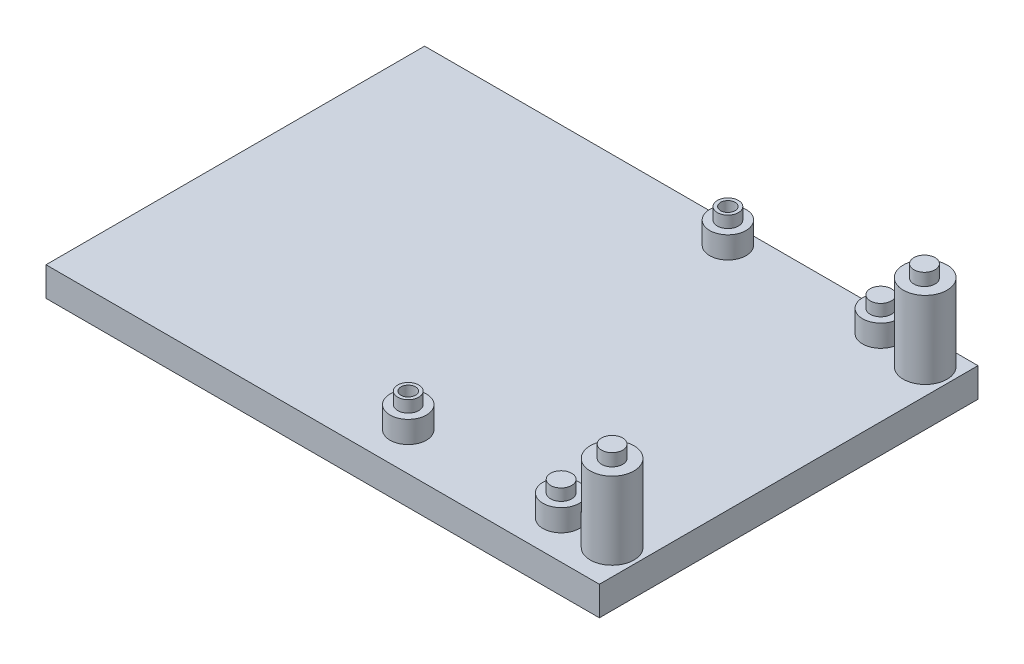
SolidWorks part; units mm, degrees
ref_plane "Front Plane" through (0, 0, 0) normal (0, 0, 1) x (1, 0, 0)
ref_plane "Top Plane" through (0, 0, 0) normal (0, 1, 0) x (1, 0, 0)
ref_plane "Right Plane" through (0, 0, 0) normal (1, 0, 0) x (0, 0, -1)
sketch "Sketch1" plane through (0, 0, 0) normal (0, 1, 0) x (1, 0, 0)
  line L0 (36, 0) -> (36, 44) construction
  line L1 (0, 0) -> (72, 0)
  line L2 (0, 0) -> (0, 44)
  line L3 (0, 44) -> (72, 44)
  line L4 (72, 0) -> (72, 44)
  line L6 (-2, -2) -> (74, -2)
  line L7 (-2, -2) -> (-2, 46)
  line L8 (-2, 46) -> (74, 46)
  line L9 (74, -2) -> (74, 46)
  line L10 (-2, -2) -> (74, 46) construction
  line L11 (-2, 46) -> (74, -2) construction
  point P7 (36, 22)
  dimension "D1" = 44
  dimension "D2" = 72
  dimension "D3" = 2
  dimension "D4" = 2
extrude "Boss-Extrude1" add sketch "Sketch1" along normal blind 2
sketch "Sketch2" plane through (0, 2, 0) normal (0, 1, 0) x (1, 0, 0)
  line L1 (-2, -2) -> (74, -2)
  line L2 (-2, -2) -> (-2, 46)
  line L3 (-2, 46) -> (74, 46)
  line L4 (74, -2) -> (74, 46)
extrude "Boss-Extrude2" add sketch "Sketch2" along normal blind 2
sketch "Sketch8" plane through (0, 0, -46) normal (0, 0, -1) x (-1, 0, 0)
  line L1 (2, 0) -> (-74, 0)
  line L2 (2, 0) -> (2, 4)
  line L3 (2, 4) -> (-74, 4)
  line L4 (-74, 0) -> (-74, 4)
extrude "Boss-Extrude7" add sketch "Sketch8" along normal blind 4
sketch "Sketch3" plane through (0, 4, 0) normal (0, 1, 0) x (1, 0, 0)
  line L0 (42.5, -2) -> (42.5, 3.25) construction
  line L1 (-2, -2) -> (74, -2) construction
  line L2 (42.5, 3.25) -> (74, 3.25) construction
  line L3 (74, -2) -> (74, 50) construction
  line L4 (42.5, 4.75) -> (42.5, 45.65) construction
  line L5 (42.5, 47.15) -> (63.5, 47.15) construction
  line L6 (63.5, 47.15) -> (63.5, 3.25) construction
  line L7 (70.5, 3.25) -> (70.5, 47.15) construction
  line L8 (70.5, 47.15) -> (63.5, 47.15) construction
  circle A0 centre (42.5, 3.25) radius 2.5
  circle A1 centre (63.5, 3.25) radius 2.5
  circle A2 centre (42.5, 47.15) radius 2.5
  circle A3 centre (63.5, 47.15) radius 2.5
  circle A4 centre (42.5, 3.25) radius 1
  circle A7 centre (42.5, 47.15) radius 1
  circle A8 centre (42.5, 47.15) radius 1.5 construction
  circle A9 centre (42.5, 3.25) radius 1.5 construction
  dimension "D3" = 5
  dimension "D4" = 2
  dimension "D6" = 3
  dimension "D8" = 3.5
  dimension "D2" = 5.25
  dimension "D5" = 21
  dimension "D7" = 40.9
  dimension "D9" = 28
extrude "Boss-Extrude3" add sketch "Sketch3" along normal blind 3
sketch "Sketch4" plane through (0, 7, 0) normal (0, 1, 0) x (1, 0, 0)
  circle A0 centre (42.5, 3.25) radius 1
  circle A1 centre (42.5, 3.25) radius 1.45
  circle A5 centre (42.5, 47.15) radius 1.45
  circle A8 centre (42.5, 47.15) radius 1
  circle A9 centre (63.5, 3.25) radius 1.45
  circle A10 centre (63.5, 47.15) radius 1.45
  dimension "D1" = 2.9
extrude "Boss-Extrude4" add sketch "Sketch4" along normal blind 1.6
sketch "Sketch5" plane through (0, 4, 0) normal (0, 1, 0) x (1, 0, 0)
  circle A0 centre (70.5, 3.25) radius 3
  circle A1 centre (70.5, 46.25) radius 3
  dimension "D2" = 6
  dimension "D1" = 43
extrude "Boss-Extrude5" add sketch "Sketch5" along normal blind 10.6
sketch "Sketch7" plane through (0, 14.6, 0) normal (0, 1, 0) x (1, 0, 0)
  line L0 (70.5, 46.25) -> (70.5, 46.15) construction
  circle A0 centre (70.5, 3.25) radius 1.45
  circle A1 centre (70.5, 46.15) radius 1.45
  circle A2 centre (70.5, 3.25) radius 3 construction
  dimension "D1" = 2.9
  dimension "D2" = 0.1
extrude "Boss-Extrude6" add sketch "Sketch7" along normal blind 1.7
sketch "Sketch9" plane through (0, 4, 0) normal (0, 1, 0) x (1, 0, 0)
  line L0 (5.5, -2) -> (5.5, 12) construction
  line L1 (-2, -2) -> (74, -2) construction
  line L2 (5.5, 12) -> (-2, 12) construction
  line L3 (-2, 50) -> (-2, -2) construction
  line L4 (15.5, 32) -> (15.5, 12) construction
  line L5 (5.5, 12) -> (25.5, 12) construction
  line L6 (5.5, 12) -> (5.5, 32) construction
  line L7 (5.5, 32) -> (25.5, 32) construction
  line L8 (25.5, 12) -> (25.5, 32) construction
  line L9 (12, 32) -> (12, 35.1)
  line L10 (12, 35.1) -> (2.4, 35.1)
  line L11 (2.4, 35.1) -> (2.4, 8.9)
  line L12 (2.4, 8.9) -> (12, 8.9)
  line L13 (12, 8.9) -> (12, 12)
  line L17 (5.5, 12) -> (2.4, 8.9) construction
  line L18 (5.5, 32) -> (2.4, 35.1) construction
  line L19 (12, 32) -> (12, 12)
  line L20 (5.5, 32) -> (12, 32) construction
  line L21 (12, 12) -> (5.5, 12) construction
  line L22 (5.5, 12) -> (5.5, 32) construction
  line L23 (19, 32) -> (19, 35.1)
  line L24 (19, 35.1) -> (28.6, 35.1)
  line L25 (28.6, 35.1) -> (28.6, 8.9)
  line L26 (28.6, 8.9) -> (19, 8.9)
  line L27 (19, 8.9) -> (19, 12)
  line L28 (19, 32) -> (19, 12)
  dimension "D1" = 14
  dimension "D2" = 20
  dimension "D3" = 7.5
  dimension "D4" = 20
  dimension "D5" = 45
  dimension "D6" = 45
  dimension "D7" = 3.1
  dimension "D8" = 3.5
sketch "Sketch10" plane through (0, 4, 0) normal (0, 1, 0) x (1, 0, 0)
  line L0 (12, 35.1) -> (2.4, 35.1)
  line L2 (2.4, 35.1) -> (2.4, 8.9)
  line L3 (2.4, 8.9) -> (12, 8.9)
  line L4 (12, 8.9) -> (12, 11.9)
  line L6 (12, 11.9) -> (5.4, 11.9)
  line L7 (5.4, 11.9) -> (5.4, 32.1)
  line L8 (5.4, 32.1) -> (12, 32.1)
  line L9 (12, 32.1) -> (12, 35.1)
  line L10 (2.4, 35.1) -> (5.4, 32.1) construction
  line L11 (5.4, 11.9) -> (2.4, 8.9) construction
  line L12 (2.4, 35.1) -> (28.6, 35.1) construction
  line L13 (15.5, 35.1) -> (15.5, 12.6725) construction
  line L14 (25.6, 32.1) -> (19, 32.1)
  line L15 (19, 11.9) -> (25.6, 11.9)
  line L16 (19, 8.9) -> (19, 11.9)
  line L17 (28.6, 8.9) -> (19, 8.9)
  line L18 (19, 32.1) -> (19, 35.1)
  line L19 (19, 35.1) -> (28.6, 35.1)
  line L20 (28.6, 35.1) -> (28.6, 8.9)
  line L21 (25.6, 11.9) -> (25.6, 32.1)
  line L23 (5.5, 12) -> (5.5, 11.9) construction
  line L24 (5.5, 12) -> (5.4, 12) construction
  dimension "D1" = 3
  dimension "D2" = 45
  dimension "D3" = 0.1
  dimension "D4" = 0.1
  dimension "D5" = 3.5
extrude "Boss-Extrude9" [suppressed] add sketch "Sketch10" along normal blind 5
